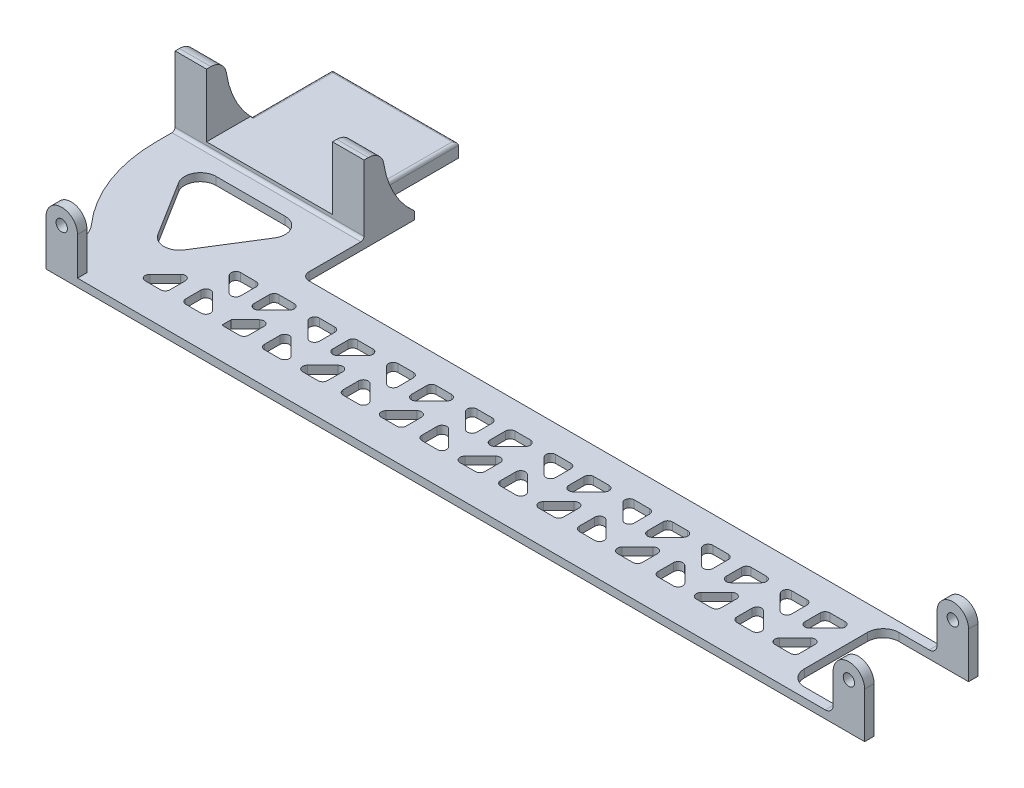
SolidWorks part; units mm, degrees
ref_plane "Front" through (0, 0, 0) normal (0, 0, 1) x (1, 0, 0)
ref_plane "Top" through (0, 0, 0) normal (0, 1, 0) x (1, 0, 0)
ref_plane "Right" through (0, 0, 0) normal (1, 0, 0) x (0, 0, -1)
sketch "草图1" plane through (0, 0, 0) normal (0, 1, 0) x (1, 0, 0)
  line L1 (-125, 50) -> (125, 50)
  line L2 (-125, 50) -> (-125, -50)
  line L3 (-125, -50) -> (125, -50)
  line L4 (125, 50) -> (125, -50)
  line L5 (0, -50) -> (0, 50) construction
  line L6 (-125, 0) -> (125, 0) construction
  point P0 (0, 0)
  dimension "D1" = 250
  dimension "D2" = 100
sketch "草图2" plane through (0, 0, 0) normal (0, 0, 1) x (1, 0, 0)
  line L0 (120, 0) -> (130, 0)
  line L2 (130, 0) -> (130, 12)
  line L3 (130, 12) -> (120, 12)
  line L4 (120, 12) -> (120, 0)
  line L5 (-125, 0) -> (125, 0) construction
  line L6 (-125, 0) -> (125, 0)
  circle A0 centre (125, 12) radius 5
  circle A1 centre (125, 12) radius 1.8
  point P3 (125, 0)
  dimension "D3" = 3.6
  dimension "D1" = 10
  dimension "D2" = 12
extrude "凸台-拉伸2" add sketch "草图2" along normal mid plane 36 contours A1 L3 A0 | A1 L3 A0 | A0 L4 L0 L2
sketch "草图3" plane through (0, 0, 0) normal (0, 1, 0) x (1, 0, 0)
  line L1 (-135, 38) -> (-95, 38)
  line L2 (-125, 0) -> (125, 0) construction
  line L3 (-125, 50) -> (-125, -50) construction
  line L5 (-95, 38) -> (-85, 38)
  line L6 (-95, 38) -> (-95, 54)
  line L7 (-95, 54) -> (-85, 54)
  line L8 (-85, 38) -> (-85, 54)
  line L9 (-135, 38) -> (-145, 38)
  line L10 (-135, 38) -> (-135, 54)
  line L11 (-135, 54) -> (-145, 54)
  line L12 (-145, 38) -> (-145, 54)
  point P4 (-125, 38)
  dimension "D1" = 38
  dimension "D2" = 30
  dimension "D3" = 10
  dimension "D4" = 16
  dimension "D5" = 10
  dimension "D6" = 16
  dimension "D7" = 10
extrude "凸台-拉伸3" add sketch "草图3" along normal blind 22 separate body contours L5 L8 L7 L6 | L12 L9 L10 L11
sketch "草图7" plane through (-145, 0, 0) normal (-1, 0, 0) x (0, 0, 1)
  line L0 (-38, 22) -> (-54, 22) construction
  line L1 (-44, 22) -> (-44, 0) construction
  line L5 (-54, 0) -> (-38, 0)
  line L6 (-38, 0) -> (-38, 22)
  line L7 (-38, 22) -> (-54, 22)
  line L8 (-54, 22) -> (-54, 0)
  line L9 (-54, 0) -> (-38, 0)
  line L10 (-38, 0) -> (-38, 22)
  line L11 (-38, 22) -> (-54, 22)
  line L12 (-54, 22) -> (-54, 0)
  arc A0 (-44, 22) -> (-54, 0) centre (-73.2, 22) cw
  point P0 (-44, 22)
  line M10 (-54, 22) -> (-54, 0)
  dimension "D1" = 6
  dimension "D2" = 0
extrude "切除-拉伸2" cut sketch "草图7" against normal blind 60 contours A0 L11 M10
fillet "圆角1" radius 5 1 edges at (-140, 22, -44)
fillet "圆角2" radius 5 1 edges at (-90, 22, -44)
sketch "草图10" plane through (0, 0, 0) normal (0, 1, 0) x (1, 0, 0)
  line L0 (-95, 38) -> (-95, 54) construction
  line L1 (-135, 38) -> (-135, 54) construction
  line L2 (-95, 38) -> (-95, 54)
  line L3 (-135, 38) -> (-135, 54)
  line L4 (-135, 38) -> (-95, 38)
  line L6 (-135, 54) -> (-135, 78)
  line L7 (-135, 78) -> (-95, 78)
  line L8 (-95, 78) -> (-95, 54)
  dimension "D1" = 40
extrude "凸台-拉伸4" add sketch "草图10" along normal blind 2
sketch "草图11" plane through (0, 0, 0) normal (0, 1, 0) x (1, 0, 0)
  line L0 (120, -18) -> (-95, -18)
  line L1 (-145, 32) -> (-145, 38)
  line L2 (120, 18) -> (-85, 18)
  line L3 (-85, 18) -> (-85, 38)
  line L4 (130, 18) -> (120, 18)
  line L5 (130, -18) -> (130, 18)
  line L6 (-145, 38) -> (-85, 38)
  line L7 (-145, 54) -> (-145, 38)
  line L8 (-135, 54) -> (-145, 54)
  line L9 (-135, 78) -> (-135, 54)
  line L10 (-85, 54) -> (-95, 54)
  line L11 (-85, 38) -> (-85, 54)
  line L13 (-145, 54) -> (-145, 38)
  line L14 (-135, 54) -> (-145, 54)
  line L16 (-85, 54) -> (-95, 54)
  line L17 (-85, 38) -> (-85, 54)
  line L18 (120, -18) -> (130, -18)
  line L19 (120, 18) -> (120, -18)
  line L20 (130, 18) -> (120, 18)
  line L21 (130, -18) -> (130, 18)
  line L22 (120, -18) -> (130, -18)
  line L24 (-104.0212, 32) -> (-125.9788, 32)
  line L25 (-130.2188, 24.35) -> (-119.24, 6.784)
  line L26 (-125, 0) -> (125, 0) construction
  line L27 (-110.76, 6.784) -> (-99.7812, 24.35)
  line L28 (-135, 78) -> (-135, 54)
  line L29 (-95, 78) -> (-135, 78)
  line L30 (-95, 78) -> (-135, 78)
  line L31 (-95, 54) -> (-95, 78)
  line L32 (-95, 54) -> (-95, 78)
  line L33 (-83.5, 9.434) -> (-78.6213, 9.434)
  line L34 (-77.5607, 6.8733) -> (-82.4393, 1.9946)
  line L35 (-85, 3.0553) -> (-85, 7.934)
  line L36 (-83.5, -8) -> (-78.6213, -8)
  line L37 (-77.1213, -6.5) -> (-77.1213, -1.6213)
  line L38 (-79.682, -0.5607) -> (-84.5607, -5.4393)
  line L39 (-74.6213, -1000) -> (-74.6213, 49000) construction
  line L40 (-65.7426, -8) -> (-70.6213, -8)
  line L41 (-72.1213, -6.5) -> (-72.1213, -1.6213)
  line L42 (-69.5607, -0.5607) -> (-64.682, -5.4393)
  line L43 (-64.2426, 3.0553) -> (-64.2426, 7.934)
  line L44 (-65.7426, 9.434) -> (-70.6213, 9.434)
  line L45 (-71.682, 6.8733) -> (-66.8033, 1.9946)
  line L46 (-83.5, 7.934) -> (-83.5, 3.0553) construction
  line L47 (-40.7426, 9.434) -> (-45.6213, 9.434)
  line L48 (-39.2426, 3.0553) -> (-39.2426, 7.934)
  line L49 (-46.682, 6.8733) -> (-41.8033, 1.9946)
  line L50 (-44.5607, -0.5607) -> (-39.682, -5.4393)
  line L51 (-47.1213, -6.5) -> (-47.1213, -1.6213)
  line L52 (-40.7426, -8) -> (-45.6213, -8)
  line L53 (-52.5607, 6.8733) -> (-57.4393, 1.9946)
  line L54 (-58.5, 9.434) -> (-53.6213, 9.434)
  line L55 (-60, 3.0553) -> (-60, 7.934)
  line L56 (-54.682, -0.5607) -> (-59.5607, -5.4393)
  line L57 (-52.1213, -6.5) -> (-52.1213, -1.6213)
  line L58 (-58.5, -8) -> (-53.6213, -8)
  line L59 (-15.7426, 9.434) -> (-20.6213, 9.434)
  line L60 (-14.2426, 3.0553) -> (-14.2426, 7.934)
  line L61 (-21.682, 6.8733) -> (-16.8033, 1.9946)
  line L62 (-19.5607, -0.5607) -> (-14.682, -5.4393)
  line L63 (-22.1213, -6.5) -> (-22.1213, -1.6213)
  line L64 (-15.7426, -8) -> (-20.6213, -8)
  line L65 (-27.5607, 6.8733) -> (-32.4393, 1.9946)
  line L66 (-33.5, 9.434) -> (-28.6213, 9.434)
  line L67 (-35, 3.0553) -> (-35, 7.934)
  line L68 (-29.682, -0.5607) -> (-34.5607, -5.4393)
  line L69 (-27.1213, -6.5) -> (-27.1213, -1.6213)
  line L70 (-33.5, -8) -> (-28.6213, -8)
  line L71 (9.2574, 9.434) -> (4.3787, 9.434)
  line L72 (10.7574, 3.0553) -> (10.7574, 7.934)
  line L73 (3.318, 6.8733) -> (8.1967, 1.9946)
  line L74 (5.4393, -0.5607) -> (10.318, -5.4393)
  line L75 (2.8787, -6.5) -> (2.8787, -1.6213)
  line L76 (9.2574, -8) -> (4.3787, -8)
  line L77 (-2.5607, 6.8733) -> (-7.4393, 1.9946)
  line L78 (-8.5, 9.434) -> (-3.6213, 9.434)
  line L79 (-10, 3.0553) -> (-10, 7.934)
  line L80 (-4.682, -0.5607) -> (-9.5607, -5.4393)
  line L81 (-2.1213, -6.5) -> (-2.1213, -1.6213)
  line L82 (-8.5, -8) -> (-3.6213, -8)
  line L83 (34.2574, 9.434) -> (29.3787, 9.434)
  line L84 (35.7574, 3.0553) -> (35.7574, 7.934)
  line L85 (28.318, 6.8733) -> (33.1967, 1.9946)
  line L86 (30.4393, -0.5607) -> (35.318, -5.4393)
  line L87 (27.8787, -6.5) -> (27.8787, -1.6213)
  line L88 (34.2574, -8) -> (29.3787, -8)
  line L89 (22.4393, 6.8733) -> (17.5607, 1.9946)
  line L90 (16.5, 9.434) -> (21.3787, 9.434)
  line L91 (15, 3.0553) -> (15, 7.934)
  line L92 (20.318, -0.5607) -> (15.4393, -5.4393)
  line L93 (22.8787, -6.5) -> (22.8787, -1.6213)
  line L94 (16.5, -8) -> (21.3787, -8)
  line L95 (59.2574, 9.434) -> (54.3787, 9.434)
  line L96 (60.7574, 3.0553) -> (60.7574, 7.934)
  line L97 (53.318, 6.8733) -> (58.1967, 1.9946)
  line L98 (55.4393, -0.5607) -> (60.318, -5.4393)
  line L99 (52.8787, -6.5) -> (52.8787, -1.6213)
  line L100 (59.2574, -8) -> (54.3787, -8)
  line L101 (47.4393, 6.8733) -> (42.5607, 1.9946)
  line L102 (41.5, 9.434) -> (46.3787, 9.434)
  line L103 (40, 3.0553) -> (40, 7.934)
  line L104 (45.318, -0.5607) -> (40.4393, -5.4393)
  line L105 (47.8787, -6.5) -> (47.8787, -1.6213)
  line L106 (41.5, -8) -> (46.3787, -8)
  line L107 (84.2574, 9.434) -> (79.3787, 9.434)
  line L108 (85.7574, 3.0553) -> (85.7574, 7.934)
  line L109 (78.318, 6.8733) -> (83.1967, 1.9946)
  line L110 (80.4393, -0.5607) -> (85.318, -5.4393)
  line L111 (77.8787, -6.5) -> (77.8787, -1.6213)
  line L112 (84.2574, -8) -> (79.3787, -8)
  line L113 (72.4393, 6.8733) -> (67.5607, 1.9946)
  line L114 (66.5, 9.434) -> (71.3787, 9.434)
  line L115 (65, 3.0553) -> (65, 7.934)
  line L116 (70.318, -0.5607) -> (65.4393, -5.4393)
  line L117 (72.8787, -6.5) -> (72.8787, -1.6213)
  line L118 (66.5, -8) -> (71.3787, -8)
  line L119 (109.2574, 9.434) -> (104.3787, 9.434)
  line L120 (110.7574, 3.0553) -> (110.7574, 7.934)
  line L121 (103.318, 6.8733) -> (108.1967, 1.9946)
  line L122 (105.4393, -0.5607) -> (110.318, -5.4393)
  line L123 (102.8787, -6.5) -> (102.8787, -1.6213)
  line L124 (109.2574, -8) -> (104.3787, -8)
  line L125 (97.4393, 6.8733) -> (92.5607, 1.9946)
  line L126 (91.5, 9.434) -> (96.3787, 9.434)
  line L127 (90, 3.0553) -> (90, 7.934)
  line L128 (95.318, -0.5607) -> (90.4393, -5.4393)
  line L129 (97.8787, -6.5) -> (97.8787, -1.6213)
  line L130 (91.5, -8) -> (96.3787, -8)
  line L131 (-90.7426, 9.434) -> (-95.6213, 9.434)
  line L132 (-89.2426, 3.0553) -> (-89.2426, 7.934)
  line L133 (-96.682, 6.8733) -> (-91.8033, 1.9946)
  line L134 (-94.5607, -0.5607) -> (-89.682, -5.4393)
  line L135 (-97.1213, -6.5) -> (-97.1213, -1.6213)
  line L136 (-90.7426, -8) -> (-95.6213, -8)
  line L140 (-108.5, -8) -> (-103.6213, -8)
  line L141 (-102.1213, -6.5) -> (-102.1213, -1.6213)
  line L142 (-104.682, -0.5607) -> (-109.5607, -5.4393)
  line L143 (-102.5607, 6.8733) -> (-107.4393, 1.9946) [skipped]
  line L144 (-110, 3.0553) -> (-110, 7.934) [skipped]
  line L145 (-108.5, 9.434) -> (-103.6213, 9.434) [skipped]
  arc A0 (-145, 32) -> (-95, -18) centre (-95, 32) ccw
  arc A1 (-119.24, 6.784) -> (-110.76, 6.784) centre (-115, 9.434) ccw
  arc A2 (-125.9788, 32) -> (-130.2188, 24.35) centre (-125.9788, 27) ccw
  arc A3 (-99.7812, 24.35) -> (-104.0212, 32) centre (-104.0212, 27) ccw
  arc A4 (-83.5, -8) -> (-84.5607, -5.4393) centre (-83.5, -6.5) cw
  arc A5 (-77.1213, -6.5) -> (-78.6213, -8) centre (-78.6213, -6.5) cw
  arc A6 (-77.1213, -1.6213) -> (-79.682, -0.5607) centre (-78.6213, -1.6213) ccw
  arc A7 (-85, 7.934) -> (-83.5, 9.434) centre (-83.5, 7.934) cw
  arc A8 (-85, 3.0553) -> (-82.4393, 1.9946) centre (-83.5, 3.0553) ccw
  arc A9 (-77.5607, 6.8733) -> (-78.6213, 9.434) centre (-78.6213, 7.934) ccw
  arc A10 (-65.7426, -8) -> (-64.682, -5.4393) centre (-65.7426, -6.5) ccw
  arc A11 (-72.1213, -6.5) -> (-70.6213, -8) centre (-70.6213, -6.5) ccw
  arc A12 (-72.1213, -1.6213) -> (-69.5607, -0.5607) centre (-70.6213, -1.6213) cw
  arc A13 (-64.2426, 3.0553) -> (-66.8033, 1.9946) centre (-65.7426, 3.0553) cw
  arc A14 (-64.2426, 7.934) -> (-65.7426, 9.434) centre (-65.7426, 7.934) ccw
  arc A15 (-71.682, 6.8733) -> (-70.6213, 9.434) centre (-70.6213, 7.934) cw
  arc A16 (-39.2426, 7.934) -> (-40.7426, 9.434) centre (-40.7426, 7.934) ccw
  arc A17 (-39.2426, 3.0553) -> (-41.8033, 1.9946) centre (-40.7426, 3.0553) cw
  arc A18 (-46.682, 6.8733) -> (-45.6213, 9.434) centre (-45.6213, 7.934) cw
  arc A19 (-47.1213, -1.6213) -> (-44.5607, -0.5607) centre (-45.6213, -1.6213) cw
  arc A20 (-47.1213, -6.5) -> (-45.6213, -8) centre (-45.6213, -6.5) ccw
  arc A21 (-40.7426, -8) -> (-39.682, -5.4393) centre (-40.7426, -6.5) ccw
  arc A22 (-52.5607, 6.8733) -> (-53.6213, 9.434) centre (-53.6213, 7.934) ccw
  arc A23 (-60, 7.934) -> (-58.5, 9.434) centre (-58.5, 7.934) cw
  arc A24 (-60, 3.0553) -> (-57.4393, 1.9946) centre (-58.5, 3.0553) ccw
  arc A25 (-52.1213, -1.6213) -> (-54.682, -0.5607) centre (-53.6213, -1.6213) ccw
  arc A26 (-52.1213, -6.5) -> (-53.6213, -8) centre (-53.6213, -6.5) cw
  arc A27 (-58.5, -8) -> (-59.5607, -5.4393) centre (-58.5, -6.5) cw
  arc A28 (-14.2426, 7.934) -> (-15.7426, 9.434) centre (-15.7426, 7.934) ccw
  arc A29 (-14.2426, 3.0553) -> (-16.8033, 1.9946) centre (-15.7426, 3.0553) cw
  arc A30 (-21.682, 6.8733) -> (-20.6213, 9.434) centre (-20.6213, 7.934) cw
  arc A31 (-22.1213, -1.6213) -> (-19.5607, -0.5607) centre (-20.6213, -1.6213) cw
  arc A32 (-22.1213, -6.5) -> (-20.6213, -8) centre (-20.6213, -6.5) ccw
  arc A33 (-15.7426, -8) -> (-14.682, -5.4393) centre (-15.7426, -6.5) ccw
  arc A34 (-27.5607, 6.8733) -> (-28.6213, 9.434) centre (-28.6213, 7.934) ccw
  arc A35 (-35, 7.934) -> (-33.5, 9.434) centre (-33.5, 7.934) cw
  arc A36 (-35, 3.0553) -> (-32.4393, 1.9946) centre (-33.5, 3.0553) ccw
  arc A37 (-27.1213, -1.6213) -> (-29.682, -0.5607) centre (-28.6213, -1.6213) ccw
  arc A38 (-27.1213, -6.5) -> (-28.6213, -8) centre (-28.6213, -6.5) cw
  arc A39 (-33.5, -8) -> (-34.5607, -5.4393) centre (-33.5, -6.5) cw
  arc A40 (10.7574, 7.934) -> (9.2574, 9.434) centre (9.2574, 7.934) ccw
  arc A41 (10.7574, 3.0553) -> (8.1967, 1.9946) centre (9.2574, 3.0553) cw
  arc A42 (3.318, 6.8733) -> (4.3787, 9.434) centre (4.3787, 7.934) cw
  arc A43 (2.8787, -1.6213) -> (5.4393, -0.5607) centre (4.3787, -1.6213) cw
  arc A44 (2.8787, -6.5) -> (4.3787, -8) centre (4.3787, -6.5) ccw
  arc A45 (9.2574, -8) -> (10.318, -5.4393) centre (9.2574, -6.5) ccw
  arc A46 (-2.5607, 6.8733) -> (-3.6213, 9.434) centre (-3.6213, 7.934) ccw
  arc A47 (-10, 7.934) -> (-8.5, 9.434) centre (-8.5, 7.934) cw
  arc A48 (-10, 3.0553) -> (-7.4393, 1.9946) centre (-8.5, 3.0553) ccw
  arc A49 (-2.1213, -1.6213) -> (-4.682, -0.5607) centre (-3.6213, -1.6213) ccw
  arc A50 (-2.1213, -6.5) -> (-3.6213, -8) centre (-3.6213, -6.5) cw
  arc A51 (-8.5, -8) -> (-9.5607, -5.4393) centre (-8.5, -6.5) cw
  arc A52 (35.7574, 7.934) -> (34.2574, 9.434) centre (34.2574, 7.934) ccw
  arc A53 (35.7574, 3.0553) -> (33.1967, 1.9946) centre (34.2574, 3.0553) cw
  arc A54 (28.318, 6.8733) -> (29.3787, 9.434) centre (29.3787, 7.934) cw
  arc A55 (27.8787, -1.6213) -> (30.4393, -0.5607) centre (29.3787, -1.6213) cw
  arc A56 (27.8787, -6.5) -> (29.3787, -8) centre (29.3787, -6.5) ccw
  arc A57 (34.2574, -8) -> (35.318, -5.4393) centre (34.2574, -6.5) ccw
  arc A58 (22.4393, 6.8733) -> (21.3787, 9.434) centre (21.3787, 7.934) ccw
  arc A59 (15, 7.934) -> (16.5, 9.434) centre (16.5, 7.934) cw
  arc A60 (15, 3.0553) -> (17.5607, 1.9946) centre (16.5, 3.0553) ccw
  arc A61 (22.8787, -1.6213) -> (20.318, -0.5607) centre (21.3787, -1.6213) ccw
  arc A62 (22.8787, -6.5) -> (21.3787, -8) centre (21.3787, -6.5) cw
  arc A63 (16.5, -8) -> (15.4393, -5.4393) centre (16.5, -6.5) cw
  arc A64 (60.7574, 7.934) -> (59.2574, 9.434) centre (59.2574, 7.934) ccw
  arc A65 (60.7574, 3.0553) -> (58.1967, 1.9946) centre (59.2574, 3.0553) cw
  arc A66 (53.318, 6.8733) -> (54.3787, 9.434) centre (54.3787, 7.934) cw
  arc A67 (52.8787, -1.6213) -> (55.4393, -0.5607) centre (54.3787, -1.6213) cw
  arc A68 (52.8787, -6.5) -> (54.3787, -8) centre (54.3787, -6.5) ccw
  arc A69 (59.2574, -8) -> (60.318, -5.4393) centre (59.2574, -6.5) ccw
  arc A70 (47.4393, 6.8733) -> (46.3787, 9.434) centre (46.3787, 7.934) ccw
  arc A71 (40, 7.934) -> (41.5, 9.434) centre (41.5, 7.934) cw
  arc A72 (40, 3.0553) -> (42.5607, 1.9946) centre (41.5, 3.0553) ccw
  arc A73 (47.8787, -1.6213) -> (45.318, -0.5607) centre (46.3787, -1.6213) ccw
  arc A74 (47.8787, -6.5) -> (46.3787, -8) centre (46.3787, -6.5) cw
  arc A75 (41.5, -8) -> (40.4393, -5.4393) centre (41.5, -6.5) cw
  arc A76 (85.7574, 7.934) -> (84.2574, 9.434) centre (84.2574, 7.934) ccw
  arc A77 (85.7574, 3.0553) -> (83.1967, 1.9946) centre (84.2574, 3.0553) cw
  arc A78 (78.318, 6.8733) -> (79.3787, 9.434) centre (79.3787, 7.934) cw
  arc A79 (77.8787, -1.6213) -> (80.4393, -0.5607) centre (79.3787, -1.6213) cw
  arc A80 (77.8787, -6.5) -> (79.3787, -8) centre (79.3787, -6.5) ccw
  arc A81 (84.2574, -8) -> (85.318, -5.4393) centre (84.2574, -6.5) ccw
  arc A82 (72.4393, 6.8733) -> (71.3787, 9.434) centre (71.3787, 7.934) ccw
  arc A83 (65, 7.934) -> (66.5, 9.434) centre (66.5, 7.934) cw
  arc A84 (65, 3.0553) -> (67.5607, 1.9946) centre (66.5, 3.0553) ccw
  arc A85 (72.8787, -1.6213) -> (70.318, -0.5607) centre (71.3787, -1.6213) ccw
  arc A86 (72.8787, -6.5) -> (71.3787, -8) centre (71.3787, -6.5) cw
  arc A87 (66.5, -8) -> (65.4393, -5.4393) centre (66.5, -6.5) cw
  arc A88 (110.7574, 7.934) -> (109.2574, 9.434) centre (109.2574, 7.934) ccw
  arc A89 (110.7574, 3.0553) -> (108.1967, 1.9946) centre (109.2574, 3.0553) cw
  arc A90 (103.318, 6.8733) -> (104.3787, 9.434) centre (104.3787, 7.934) cw
  arc A91 (102.8787, -1.6213) -> (105.4393, -0.5607) centre (104.3787, -1.6213) cw
  arc A92 (102.8787, -6.5) -> (104.3787, -8) centre (104.3787, -6.5) ccw
  arc A93 (109.2574, -8) -> (110.318, -5.4393) centre (109.2574, -6.5) ccw
  arc A94 (97.4393, 6.8733) -> (96.3787, 9.434) centre (96.3787, 7.934) ccw
  arc A95 (90, 7.934) -> (91.5, 9.434) centre (91.5, 7.934) cw
  arc A96 (90, 3.0553) -> (92.5607, 1.9946) centre (91.5, 3.0553) ccw
  arc A97 (97.8787, -1.6213) -> (95.318, -0.5607) centre (96.3787, -1.6213) ccw
  arc A98 (97.8787, -6.5) -> (96.3787, -8) centre (96.3787, -6.5) cw
  arc A99 (91.5, -8) -> (90.4393, -5.4393) centre (91.5, -6.5) cw
  arc A100 (-89.2426, 7.934) -> (-90.7426, 9.434) centre (-90.7426, 7.934) ccw
  arc A101 (-89.2426, 3.0553) -> (-91.8033, 1.9946) centre (-90.7426, 3.0553) cw
  arc A102 (-96.682, 6.8733) -> (-95.6213, 9.434) centre (-95.6213, 7.934) cw
  arc A103 (-97.1213, -1.6213) -> (-94.5607, -0.5607) centre (-95.6213, -1.6213) cw
  arc A104 (-97.1213, -6.5) -> (-95.6213, -8) centre (-95.6213, -6.5) ccw
  arc A105 (-90.7426, -8) -> (-89.682, -5.4393) centre (-90.7426, -6.5) ccw
  arc A109 (-102.1213, -6.5) -> (-103.6213, -8) centre (-103.6213, -6.5) cw
  arc A110 (-102.1213, -1.6213) -> (-104.682, -0.5607) centre (-103.6213, -1.6213) ccw
  arc A111 (-108.5, -8) -> (-109.5607, -5.4393) centre (-108.5, -6.5) cw
  arc A112 (-110, 3.0553) -> (-107.4393, 1.9946) centre (-108.5, 3.0553) ccw [skipped]
  arc A113 (-110, 7.934) -> (-108.5, 9.434) centre (-108.5, 7.934) cw [skipped]
  arc A114 (-102.5607, 6.8733) -> (-103.6213, 9.434) centre (-103.6213, 7.934) ccw [skipped]
  point P23 (-115, 0)
  point P26 (-135, 32)
  point P37 (-87.1213, -8)
  point P40 (-77.1213, -8)
  point P45 (-85, 9.434)
  point P50 (-75, 9.434)
  dimension "D3" = 50
  dimension "D5" = 5
  dimension "D10" = 1.5
  dimension "D4" = 10
  dimension "D6" = 10
  dimension "D7" = 10
  dimension "D8" = 10
  dimension "D9" = 8
  dimension "D11" = 2.5
  dimension "D12" = 4.2426
  dimension "D13" = 2
  dimension "D14" = 4.2426
  dimension "D1" = 0
  dimension "D2" = 0
fillet "圆角3" radius 1 3 edges at (-95, 2, -64.9623) (-135, 2, -64.9623) (-115, 2, -78)
extrude "凸台-拉伸5" add sketch "草图11" against normal blind 2.5
sketch "草图12" plane through (0, 0, 0) normal (0, 1, 0) x (1, 0, 0)
  line L0 (109.2574, 9.434) -> (104.3787, 9.434) construction
  line L1 (110.7574, 3.0553) -> (110.7574, 7.934) construction
  line L2 (103.318, 6.8733) -> (108.1967, 1.9946) construction
  line L3 (102.8787, -1.6213) -> (102.8787, -6.5) construction
  line L4 (130, 18) -> (120, 18)
  line L5 (120, 18) -> (120, -18)
  line L6 (120, -18) -> (130, -18)
  line L7 (130, -18) -> (130, 18)
  line L11 (130, -15) -> (130, 15)
  line L12 (104.3787, -8) -> (109.2574, -8) construction
  line L13 (110.318, -5.4393) -> (105.4393, -0.5607) construction
  line L14 (109.2574, 9.434) -> (104.3787, 9.434)
  line L15 (110.7574, 3.0553) -> (110.7574, 7.934)
  line L16 (103.318, 6.8733) -> (108.1967, 1.9946)
  line L17 (102.8787, -1.6213) -> (102.8787, -6.5)
  line L18 (104.3787, -8) -> (109.2574, -8)
  line L19 (110.318, -5.4393) -> (105.4393, -0.5607)
  line L20 (130, -15) -> (107.8787, -15)
  line L21 (102.8787, -10) -> (102.8787, 10)
  line L23 (107.8787, 15) -> (130, 15)
  line L24 (-125, 0) -> (125, 0) construction
  line L25 (-125, 0) -> (125, 0)
  arc A0 (109.2574, -8) -> (110.318, -5.4393) centre (109.2574, -6.5) ccw construction
  arc A1 (104.3787, 9.434) -> (103.318, 6.8733) centre (104.3787, 7.934) ccw construction
  arc A2 (110.7574, 7.934) -> (109.2574, 9.434) centre (109.2574, 7.934) ccw construction
  arc A3 (108.1967, 1.9946) -> (110.7574, 3.0553) centre (109.2574, 3.0553) ccw construction
  arc A4 (105.4393, -0.5607) -> (102.8787, -1.6213) centre (104.3787, -1.6213) ccw construction
  arc A5 (102.8787, -6.5) -> (104.3787, -8) centre (104.3787, -6.5) ccw construction
  arc A6 (104.3787, 9.434) -> (103.318, 6.8733) centre (104.3787, 7.934) ccw
  arc A7 (110.7574, 7.934) -> (109.2574, 9.434) centre (109.2574, 7.934) ccw
  arc A8 (108.1967, 1.9946) -> (110.7574, 3.0553) centre (109.2574, 3.0553) ccw
  arc A9 (105.4393, -0.5607) -> (102.8787, -1.6213) centre (104.3787, -1.6213) ccw
  arc A10 (102.8787, -6.5) -> (104.3787, -8) centre (104.3787, -6.5) ccw
  arc A11 (109.2574, -8) -> (110.318, -5.4393) centre (109.2574, -6.5) ccw
  arc A12 (107.8787, 15) -> (102.8787, 10) centre (107.8787, 10) ccw
  arc A13 (102.8787, -10) -> (107.8787, -15) centre (107.8787, -10) ccw
  dimension "D4" = 5
  dimension "D2" = 15
  dimension "D3" = 15
  dimension "D1" = 0
extrude "切除-拉伸10" cut sketch "草图12" against normal through all both and the other way through all
fillet "圆角4" radius 1 1 edges at (-115, 0, -38)
fillet "圆角5" radius 2.5 2 edges at (120, 0, -16.5) (120, 0, 16.5)
fillet "圆角6" radius 2.5 1 edges at (-85, -1.25, -18)
ref_plane "基准面1" through (0, 0, 15) normal (0, 0, 1) x (1, 0, 0)
sketch "草图13" plane through (0, 0, 15) normal (0, 0, 1) x (1, 0, 0)
  line L0 (-125, 0) -> (125, 0) construction
  line L1 (-125, 0) -> (125, 0)
  line L2 (-120, 0) -> (-120, 12)
  line L3 (-120, 12) -> (-130, 12)
  line L4 (-130, 12) -> (-130, 0)
  line L5 (-130, 0) -> (-125, 0)
  circle A0 centre (-125, 12) radius 5
  circle A1 centre (-125, 12) radius 1.8
  dimension "D4" = 3.6
  dimension "D1" = 5
  dimension "D2" = 5
  dimension "D3" = 12
extrude "凸台-拉伸6" add sketch "草图13" along normal blind 3 separate body contours A0 L4 L5 L1 L2 | A1 L3 A0 | A1 L3 A0
sketch "草图14" plane through (0, 0, 0) normal (0, 1, 0) x (1, 0, 0)
  line L0 (-120, -18) -> (-84.156, -18)
  line L1 (-95, -18) -> (117.5, -18) construction
  line L2 (-130, -15) -> (-130, 1.1165)
  line L3 (-130, 1.1165) -> (-84.156, 1.1165)
  line L4 (-120, -15) -> (-130, -15)
  line L5 (-120, -18) -> (-120, -15)
  line L6 (-130, -18) -> (-120, -18)
  line L7 (-130, -15) -> (-130, -18)
  line L8 (-120, -15) -> (-130, -15)
  line L9 (-120, -18) -> (-120, -15)
  line L10 (-130, -18) -> (-120, -18)
  line L11 (-130, -15) -> (-130, -18)
  line L12 (-84.156, 1.1165) -> (-84.156, -18)
  line L14 (-95.6213, -8) -> (-90.7426, -8) construction
  line L15 (-89.682, -5.4393) -> (-94.5607, -0.5607) construction
  line L16 (-97.1213, -1.6213) -> (-97.1213, -6.5) construction
  line L17 (-102.1213, -6.5) -> (-102.1213, -1.6213) construction
  line L18 (-108.5, -8) -> (-103.6213, -8) construction
  line L19 (-104.682, -0.5607) -> (-109.5607, -5.4393) construction
  line L20 (-95.6213, -8) -> (-90.7426, -8)
  line L21 (-89.682, -5.4393) -> (-94.5607, -0.5607)
  line L22 (-97.1213, -1.6213) -> (-97.1213, -6.5)
  line L23 (-102.1213, -6.5) -> (-102.1213, -1.6213)
  line L24 (-108.5, -8) -> (-103.6213, -8)
  line L25 (-104.682, -0.5607) -> (-109.5607, -5.4393)
  arc A0 (-97.1213, -6.5) -> (-95.6213, -8) centre (-95.6213, -6.5) ccw construction
  arc A1 (-90.7426, -8) -> (-89.682, -5.4393) centre (-90.7426, -6.5) ccw construction
  arc A2 (-94.5607, -0.5607) -> (-97.1213, -1.6213) centre (-95.6213, -1.6213) ccw construction
  arc A3 (-102.1213, -1.6213) -> (-104.682, -0.5607) centre (-103.6213, -1.6213) ccw construction
  arc A4 (-103.6213, -8) -> (-102.1213, -6.5) centre (-103.6213, -6.5) ccw construction
  arc A5 (-109.5607, -5.4393) -> (-108.5, -8) centre (-108.5, -6.5) ccw construction
  arc A6 (-97.1213, -6.5) -> (-95.6213, -8) centre (-95.6213, -6.5) ccw
  arc A7 (-90.7426, -8) -> (-89.682, -5.4393) centre (-90.7426, -6.5) ccw
  arc A8 (-94.5607, -0.5607) -> (-97.1213, -1.6213) centre (-95.6213, -1.6213) ccw
  arc A9 (-102.1213, -1.6213) -> (-104.682, -0.5607) centre (-103.6213, -1.6213) ccw
  arc A10 (-103.6213, -8) -> (-102.1213, -6.5) centre (-103.6213, -6.5) ccw
  arc A11 (-109.5607, -5.4393) -> (-108.5, -8) centre (-108.5, -6.5) ccw
  dimension "D2" = 45.844
  dimension "D3" = 19.1165
  dimension "D1" = 0
extrude "凸台-拉伸7" add sketch "草图14" against normal blind 2.5 contours L12 L3 L2 L8 L9 L0 A11 L25 A9 L23 A10 L24 A8 L21 A7 L20 A6 L22 | L8 L11 L10 L9
fillet "圆角7" radius 10 1 edges at (-130, -1.25, 3.7071)
